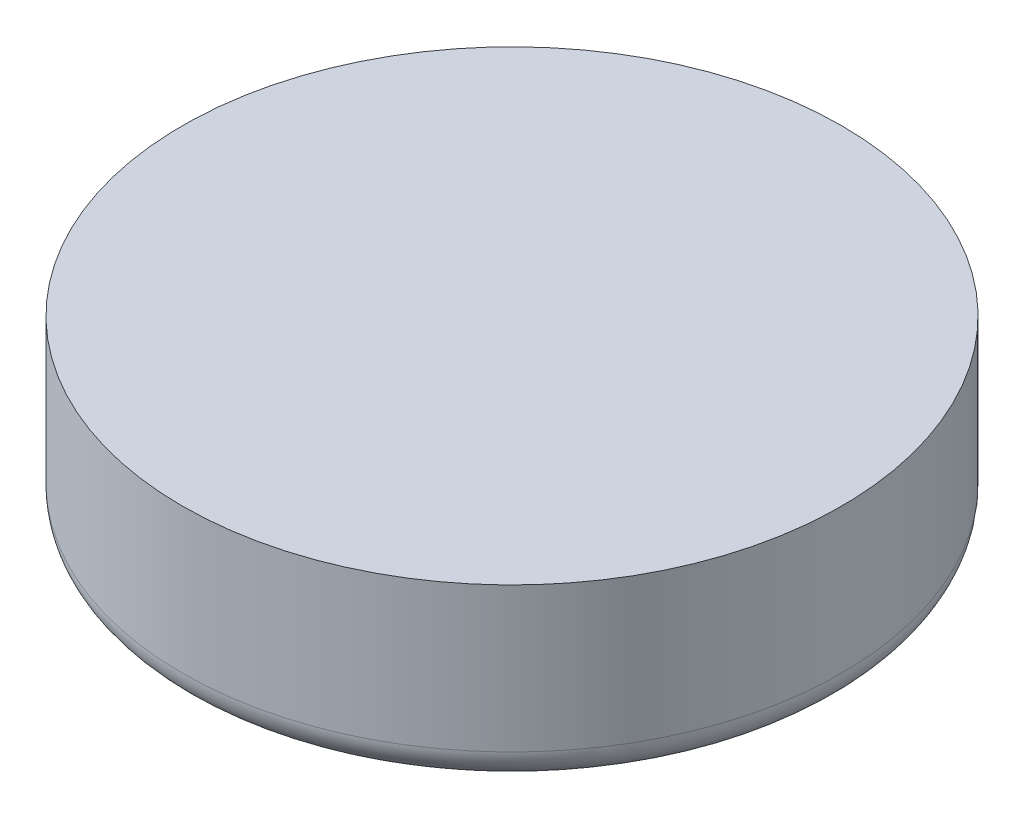
SolidWorks part; units mm, degrees
ref_plane "前视基准面" through (0, 0, 0) normal (0, 0, 1) x (1, 0, 0)
ref_plane "上视基准面" through (0, 0, 0) normal (0, 1, 0) x (1, 0, 0)
ref_plane "右视基准面" through (0, 0, 0) normal (1, 0, 0) x (0, 0, -1)
sketch "草图1" plane through (0, 0, 0) normal (0, 1, 0) x (1, 0, 0)
  circle A0 centre (0, 0) radius 2.05
  dimension "D1" = 4.1
extrude "凸台-拉伸1" add sketch "草图1" along normal blind 1.1
fillet "圆角1" radius 0.2 1 edges at (0, 0, 2.05)
